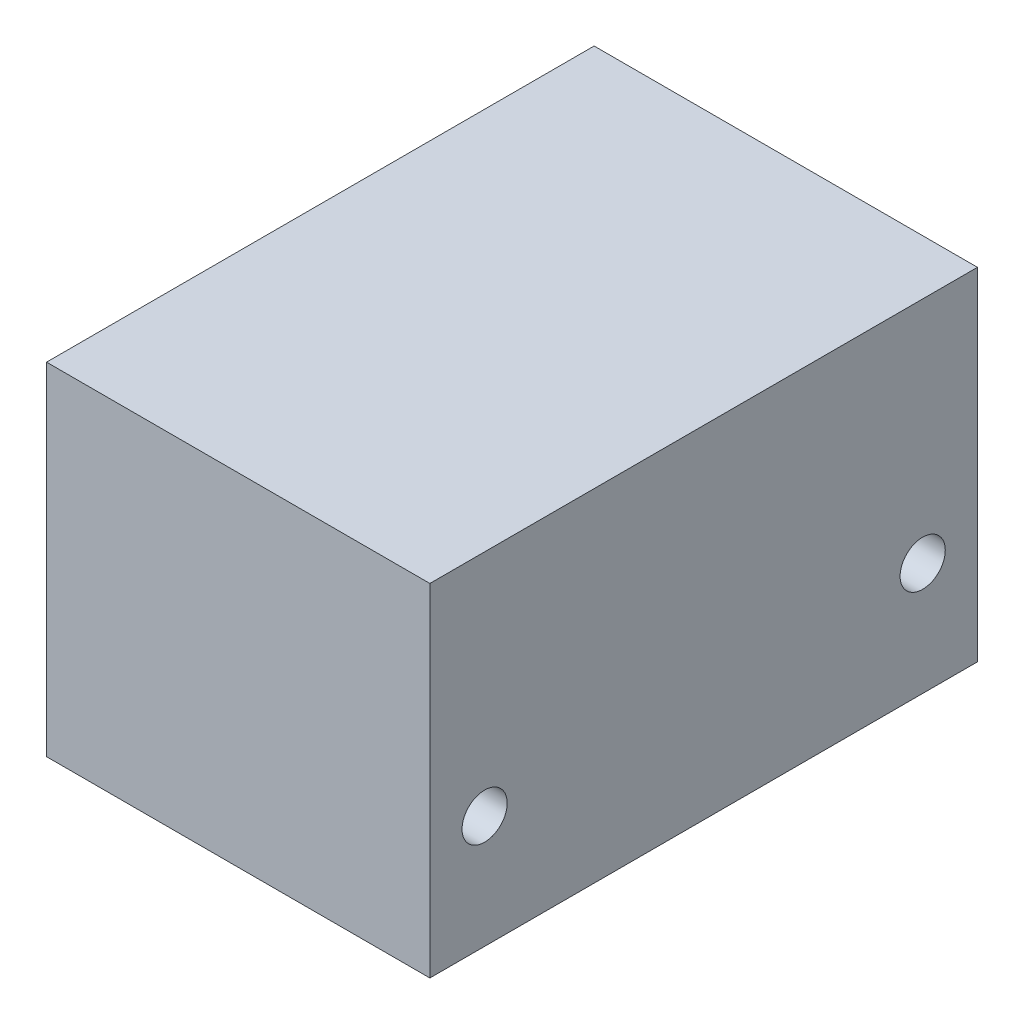
SolidWorks part; units mm, degrees
ref_plane "Front Plane" through (0, 0, 0) normal (0, 0, 1) x (1, 0, 0)
ref_plane "Top Plane" through (0, 0, 0) normal (0, 1, 0) x (1, 0, 0)
ref_plane "Right Plane" through (0, 0, 0) normal (1, 0, 0) x (0, 0, -1)
sketch "Sketch1" plane through (0, 0, 0) normal (0, 1, 0) x (1, 0, 0)
  line L1 (7, -10) -> (-7, -10)
  line L2 (7, -10) -> (7, 10)
  line L3 (7, 10) -> (-7, 10)
  line L4 (-7, -10) -> (-7, 10)
  line L5 (7, -10) -> (-7, 10) construction
  line L6 (7, 10) -> (-7, -10) construction
  point P0 (0, 0)
  dimension "D1" = 20
  dimension "D2" = 14
extrude "Boss-Extrude1" add sketch "Sketch1" along normal blind 13.98
sketch "Sketch2" plane through (7, 0, 0) normal (1, 0, 0) x (0, 0, -1)
  line L0 (0, 0) -> (0, 5.62) construction
  line L1 (-10, 0) -> (10, 0) construction
  line L2 (8, 5.62) -> (-8, 5.62) construction
  circle A0 centre (8, 5.62) radius 0.825
  circle A1 centre (-8, 5.62) radius 0.825
  point P7 (0, 5.62)
  dimension "D3" = 1.65
  dimension "D4" = 1.65
  dimension "D1" = 5.62
  dimension "D2" = 16
extrude "Cut-Extrude1" cut sketch "Sketch2" against normal through all
sketch "Sketch6" plane through (0, 0, 0) normal (0, -1, 0) x (1, 0, 0)
  line L1 (-7, 10) -> (7, 10)
  line L2 (-7, 10) -> (-7, -10)
  line L3 (-7, -10) -> (7, -10)
  line L4 (7, 10) -> (7, -10)
extrude "Cut-Extrude2" cut sketch "Sketch6" against normal blind 1.5
sketch "Sketch7" plane through (0, 1.5, 0) normal (0, -1, 0) x (1, 0, 0)
  circle A0 centre (0, 0) radius 4.55
  dimension "D1" = 9.1
extrude "Boss-Extrude2" add sketch "Sketch7" along normal blind 1.5
